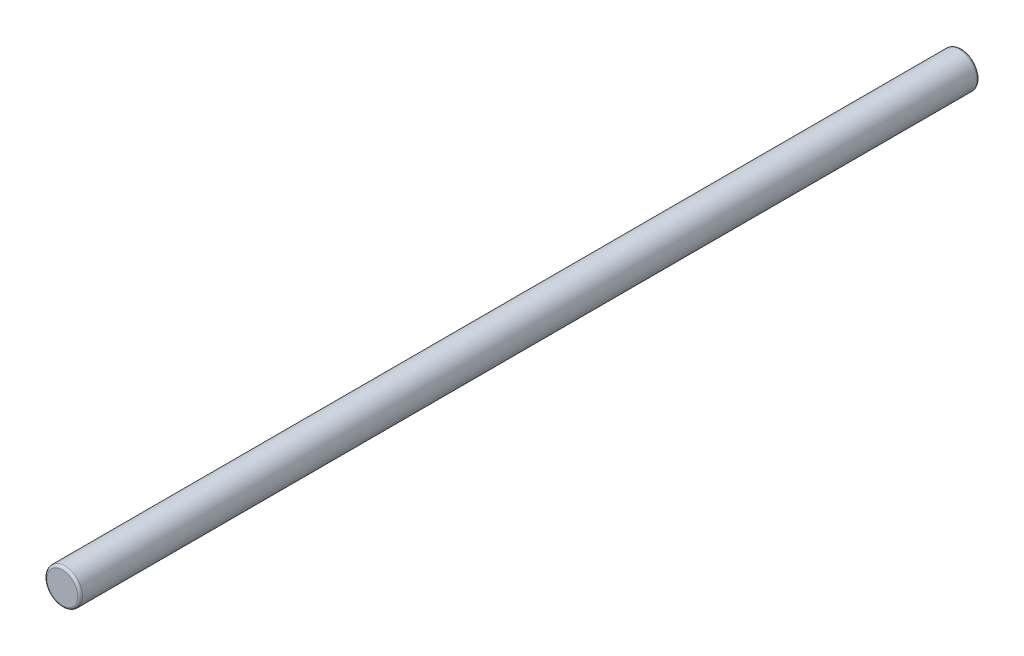
SolidWorks part; units mm, degrees
ref_plane "Plano frontal" through (0, 0, 0) normal (0, 0, 1) x (1, 0, 0)
ref_plane "Plano superior" through (0, 0, 0) normal (0, 1, 0) x (1, 0, 0)
ref_plane "Plano direito" through (0, 0, 0) normal (1, 0, 0) x (0, 0, -1)
sketch "Esboço1" plane through (0, 0, 0) normal (0, 0, 1) x (1, 0, 0)
  circle A0 centre (0, 0) radius 1.5
  dimension "D1" = 3
extrude "Ressalto-extrusão1" add sketch "Esboço1" along normal blind 76
fillet "Filete1" radius 0.2 2 edges at (1.5, 0, 0) (1.5, 0, 76)
